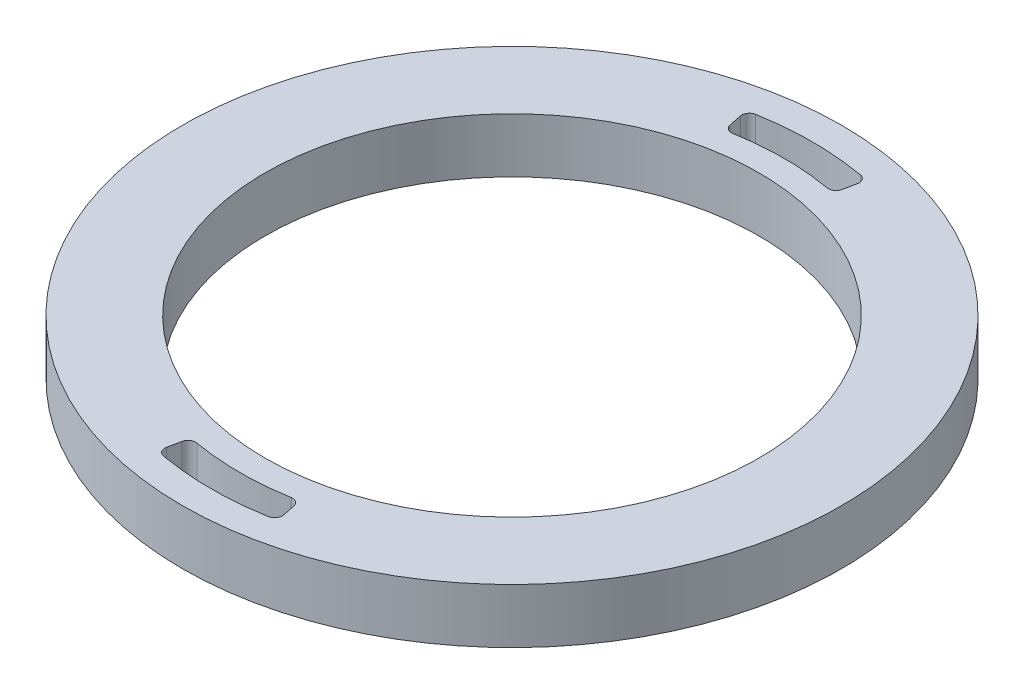
SolidWorks part; units mm, degrees
ref_plane "Front Plane" through (0, 0, 0) normal (0, 0, 1) x (1, 0, 0)
ref_plane "Top Plane" through (0, 0, 0) normal (0, 1, 0) x (1, 0, 0)
ref_plane "Right Plane" through (0, 0, 0) normal (1, 0, 0) x (0, 0, -1)
sketch "Sketch1" plane through (0, 0, 0) normal (0, 1, 0) x (1, 0, 0)
  circle A0 centre (0, 0) radius 38.2905
  circle A1 centre (0, 0) radius 28.702
  dimension "D1" = 57.404
  dimension "D2" = 76.581
extrude "Boss-Extrude1" add sketch "Sketch1" along normal blind 6.35
sketch "Sketch2" plane through (0, 6.35, 0) normal (0, 1, 0) x (1, 0, 0)
  line L0 (-6.3246, 30.9841) -> (-6.985, 34.2194)
  line L1 (6.3246, 30.9841) -> (6.985, 34.2194)
  line L2 (0, 0) -> (-6.985, -34.2194)
  line L3 (0, 0) -> (6.985, -34.2194)
  arc A2 (6.985, 34.2194) -> (-6.985, 34.2194) centre (0, 0) ccw
  arc A3 (6.3246, 30.9841) -> (-6.3246, 30.9841) centre (0, 0) ccw
  arc A4 (-6.3246, -30.9841) -> (6.3246, -30.9841) centre (0, 0) ccw
  arc A5 (-6.985, -34.2194) -> (6.985, -34.2194) centre (0, 0) ccw
  dimension "D1" = 63.246
  dimension "D2" = 69.85
  dimension "D3" = 13.97
  dimension "D4" = 6.985
  dimension "D5" = 13.97
  dimension "D6" = 6.985
extrude "Cut-Extrude1" cut sketch "Sketch2" against normal blind 6.35 contours A3 L1 A2 L0 | L2 A5 L3 A4
fillet "Fillet1" radius 0.889 8 edges at (6.3246, 3.175, 30.9841) (-6.3246, 3.175, 30.9841) (-6.985, 3.175, 34.2194) (6.985, 3.175, 34.2194) (6.3246, 3.175, -30.9841) (6.985, 3.175, -34.2194) (-6.985, 3.175, -34.2194) (-6.3246, 3.175, -30.9841)
